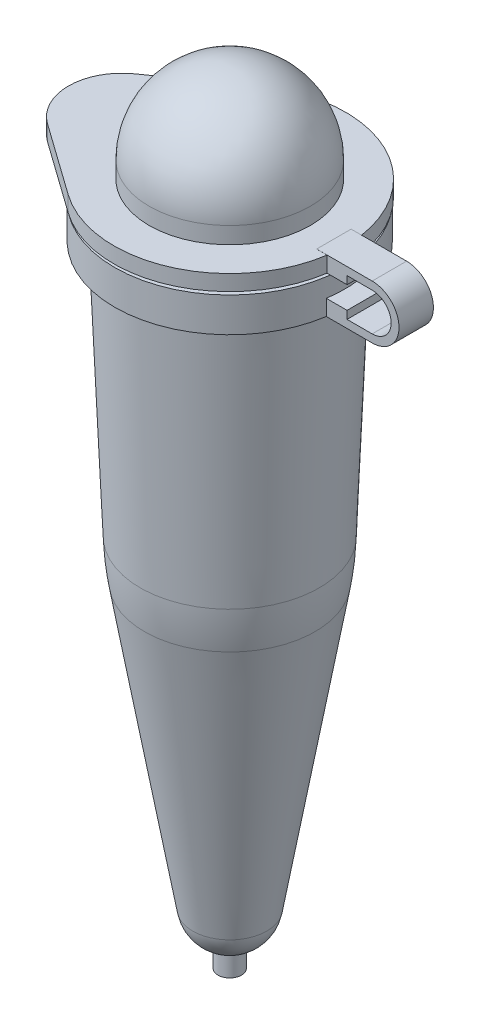
SolidWorks part; units mm, degrees
ref_plane "Front Plane" through (0, 0, 0) normal (0, 0, 1) x (1, 0, 0)
ref_plane "Top Plane" through (0, 0, 0) normal (0, 1, 0) x (1, 0, 0)
ref_plane "Right Plane" through (0, 0, 0) normal (1, 0, 0) x (0, 0, -1)
sketch "Sketch1" plane through (0, 0, 0) normal (0, 1, 0) x (1, 0, 0)
  circle A0 centre (0, 0) radius 3.7338
  circle A1 centre (0, 0) radius 2.6797
  dimension "D1" = 7.4676
  dimension "D2" = 5.3594
extrude "Boss-Extrude1" add sketch "Sketch1" against normal blind 1.1176
sketch "Sketch2" plane through (0, 0, 0) normal (0, 0, 1) x (1, 0, 0)
  line L0 (0, -1.1176) -> (0, -20.9296)
  line L1 (-3.2385, -1.1176) -> (-2.9065, -9.4171)
  line L2 (-3.7338, -1.1176) -> (3.7338, -1.1176) construction
  line L3 (-2.7708, -10.7148) -> (-1.2065, -19.911)
  line L4 (-3.2385, -1.1176) -> (0, -1.1176)
  arc A0 (-1.2065, -19.911) -> (0, -20.9296) centre (0, -19.7058) ccw
  arc A1 (-2.9065, -9.4171) -> (-2.7708, -10.7148) centre (7.2454, -9.0111) ccw
  arc A4 (0, -20.909) -> (1.2062, -19.8923) centre (0, -19.6852) ccw construction
  point P7 (-2.9591, -8.1026)
  point P10 (-2.8479, -10.2616)
  dimension "D5" = 10.16
  dimension "D1" = 3.2385
  dimension "D2" = 6.985
  dimension "D3" = 2.9591
  dimension "D4" = 9.144
  dimension "D8" = 19.812
revolve "Revolve1" add sketch "Sketch2" angle 360 about L0
shell "Shell1" thickness 0.5715
combine bodies "Combine1" operation type add bodies to combine 101 102
sketch "Sketch3" plane through (0, 0, 0) normal (0, 0, 1) x (1, 0, 0)
  line L0 (3.7338, -1.1176) -> (4.3653, -1.1176)
  line L1 (4.3653, -0.8625) -> (4.3653, -0.6074)
  line L2 (4.3653, -0.6074) -> (3.3793, -0.6074)
  line L3 (3.3793, -0.6074) -> (3.3793, -1.1176)
  line L4 (-3.7338, -1.1176) -> (3.7338, -1.1176) construction
  line L5 (3.3793, -1.1176) -> (3.7338, -1.1176)
  line L6 (4.3653, -1.1176) -> (5.18, -1.1176)
  line L8 (5.18, -0.8625) -> (4.3653, -0.8625)
  line L9 (3.3793, 0.1127) -> (4.3653, 0.1127)
  line L10 (4.3653, 0.1127) -> (4.3653, 0.3677)
  line L11 (4.3653, 0.6228) -> (3.3793, 0.6228)
  line L12 (3.3793, 0.6228) -> (3.3793, 0.1127)
  line L13 (4.3653, 0.6228) -> (5.18, 0.6228)
  line L15 (5.18, 0.3677) -> (4.3653, 0.3677)
  arc A0 (5.18, 0.6228) -> (5.18, -1.1176) centre (5.18, -0.2474) cw
  arc A1 (5.18, 0.3677) -> (5.18, -0.8625) centre (5.18, -0.2474) cw
extrude "Boss-Extrude2" add sketch "Sketch3" along normal mid plane 1.1176
sketch "Sketch4" plane through (0, 0.1127, 0) normal (0, -1, 0) x (1, 0, 0)
  circle A0 centre (0, 0) radius 2.615
  circle A1 centre (0, 0) radius 2.107
  dimension "D1" = 0.508
extrude "Boss-Extrude3" add sketch "Sketch4" along normal blind 1.1176 separate body
sketch "Sketch5" plane through (0, 0, 0) normal (0, 0, 1) x (1, 0, 0)
  line L0 (-2.615, 0.1127) -> (-2.615, 1.1608)
  line L1 (-2.107, 0.1127) -> (-2.107, 1.1608)
  line L4 (0, 3.7758) -> (0, 3.2678)
  line L5 (-2.615, 0.1127) -> (-2.615, 0.0475)
  line L6 (-2.615, 0.1127) -> (-2.615, -1.0049) construction
  line L7 (-2.615, 0.0475) -> (-2.107, 0.0475)
  line L8 (-2.107, 0.0475) -> (-2.107, 0.1127)
  arc A0 (0, 3.7758) -> (-2.615, 1.1608) centre (0, 1.1608) ccw
  arc A1 (0, 3.2678) -> (-2.107, 1.1608) centre (0, 1.1608) ccw
revolve "Revolve2" add sketch "Sketch5" angle 360 about L4
sketch "Sketch6" plane through (0, 0.1127, 0) normal (0, -1, 0) x (1, 0, 0)
  line L0 (-2.1799, -3.0626) -> (-4.5074, -1.4059)
  line L1 (0, 0) -> (1.7312, 0) construction
  line L2 (-2.1799, 3.0626) -> (-4.5074, 1.4059)
  arc A0 (-2.1799, -3.0626) -> (-2.1799, 3.0626) centre (0, 0) ccw
  arc A1 (-4.5074, 1.4059) -> (-4.5074, -1.4059) centre (-3.5067, 0) ccw
  point P5 (3.7592, 0)
  point P6 (-5.2324, 0)
  dimension "D1" = 7.5184
  dimension "D2" = 8.9916
extrude "Boss-Extrude4" add sketch "Sketch6" against normal blind 0.508
sketch "Sketch7" plane through (0, 0, 0) normal (0, 0, 1) x (1, 0, 0)
  line L1 (0, -20.6309) -> (-0.381, -20.6309)
  line L2 (0, -20.6309) -> (0, -21.5646)
  line L3 (0, -21.5646) -> (-0.381, -21.5646)
  line L4 (-0.381, -20.6309) -> (-0.381, -21.5646)
  arc A0 (-1.2065, -19.911) -> (1.2065, -19.911) centre (0, -19.7058) ccw construction
  point P4 (0, -20.9296)
  dimension "D1" = 0.635
  dimension "D2" = 0.381
revolve "Revolve3" add sketch "Sketch7" angle 360 about L2
sketch "Sketch8" plane through (0, 0.1127, 0) normal (0, -1, 0) x (1, 0, 0)
  line L0 (-5.2324, 0) -> (0, 0)
  arc A0 (-4.5074, 1.4059) -> (-4.5074, -1.4059) centre (-3.5067, 0) ccw construction
